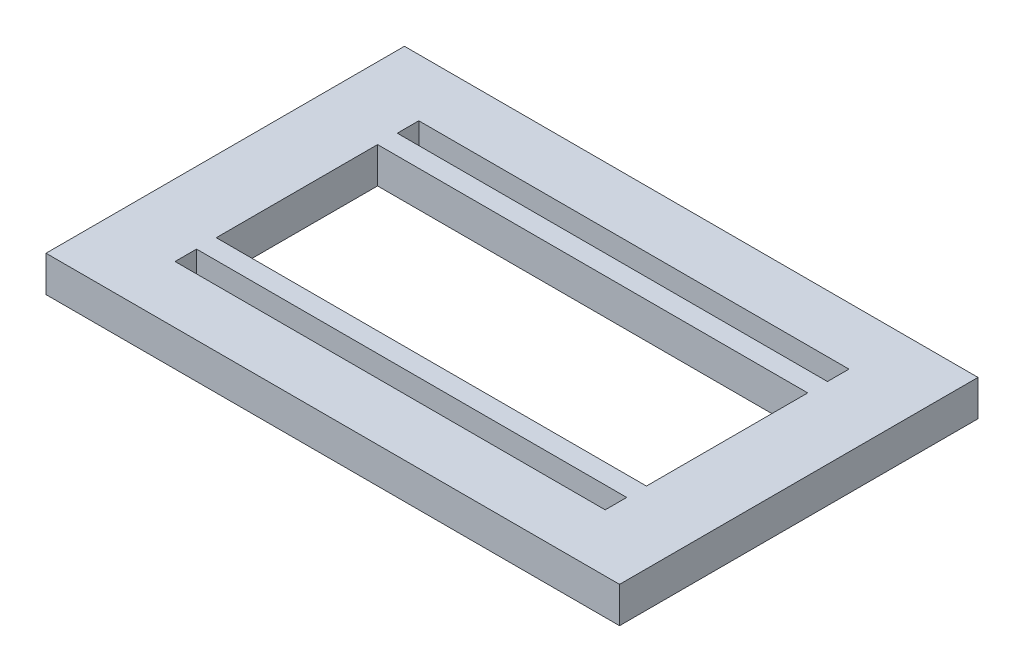
SolidWorks part; units mm, degrees
ref_plane "Front Plane" through (0, 0, 0) normal (0, 0, 1) x (1, 0, 0)
ref_plane "Top Plane" through (0, 0, 0) normal (0, 1, 0) x (1, 0, 0)
ref_plane "Right Plane" through (0, 0, 0) normal (1, 0, 0) x (0, 0, -1)
sketch "Sketch1" plane through (0, 0, 0) normal (0, 1, 0) x (1, 0, 0)
  line L0 (-40, 0) -> (40, 0) construction
  line L1 (-40, 25) -> (40, 25)
  line L2 (-40, 25) -> (-40, -25)
  line L3 (-40, -25) -> (40, -25)
  line L4 (40, 25) -> (40, -25)
  line L5 (-40, 25) -> (40, -25) construction
  line L6 (-40, -25) -> (40, 25) construction
  line L7 (-30, 17) -> (30, 17)
  line L8 (-30, 17) -> (-30, 14)
  line L9 (-30, 14) -> (30, 14)
  line L10 (30, 17) -> (30, 14)
  line L11 (-30, -17) -> (-30, -14)
  line L12 (30, -17) -> (30, -14)
  line L13 (-30, -14) -> (30, -14)
  line L14 (-30, -17) -> (30, -17)
  line L16 (-30, 11.25) -> (30, 11.25)
  line L17 (-30, 11.25) -> (-30, -11.25)
  line L18 (-30, -11.25) -> (30, -11.25)
  line L19 (30, 11.25) -> (30, -11.25)
  line L20 (-30, 11.25) -> (30, -11.25) construction
  line L21 (-30, -11.25) -> (30, 11.25) construction
  point P0 (0, 0)
  point P12 (-30, 15.5)
  point P13 (0, 14)
  point P18 (0, 0)
  dimension "D1" = 50
  dimension "D2" = 80
  dimension "D3" = 3
  dimension "D4" = 15.5
  dimension "D5" = 60
  dimension "D6" = 22.5
extrude "Boss-Extrude1" add sketch "Sketch1" along normal blind 5
